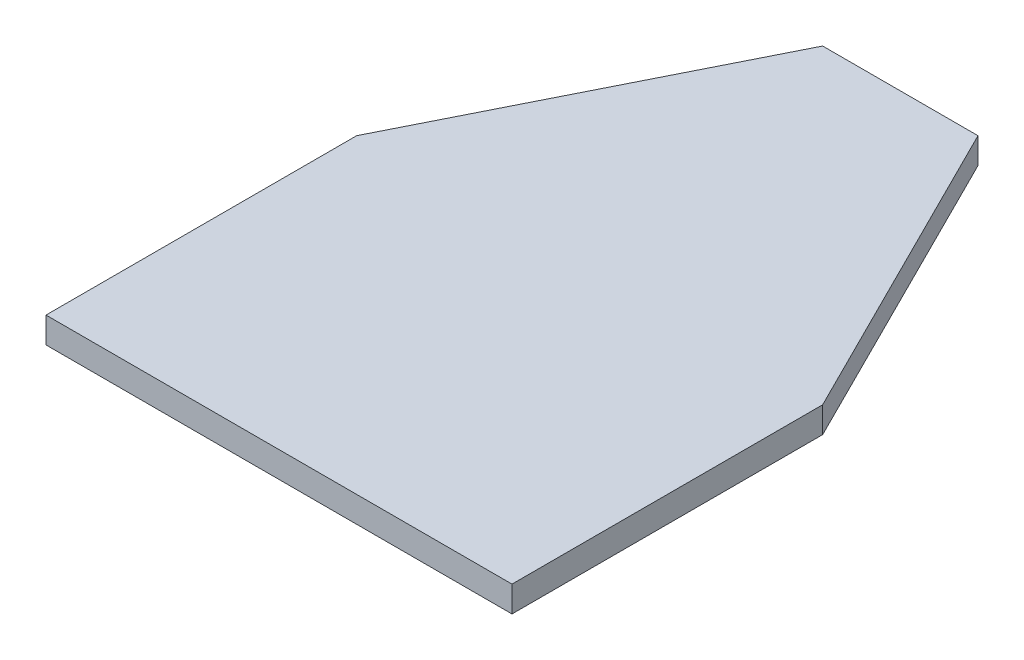
SolidWorks part; units mm, degrees
ref_plane "Front Plane" through (0, 0, 0) normal (0, 0, 1) x (1, 0, 0)
ref_plane "Top Plane" through (0, 0, 0) normal (0, 1, 0) x (1, 0, 0)
ref_plane "Right Plane" through (0, 0, 0) normal (1, 0, 0) x (0, 0, -1)
sketch "Sketch1" plane through (0, 0, 0) normal (0, 1, 0) x (1, 0, 0)
  line L0 (0, 0) -> (114.3, 0)
  line L1 (114.3, 0) -> (114.3, 76.2)
  line L2 (114.3, 76.2) -> (76.2, 152.4)
  line L3 (76.2, 152.4) -> (38.1, 152.4)
  line L4 (38.1, 152.4) -> (0, 76.2)
  line L5 (0, 76.2) -> (0, 0)
  line L6 (57.15, 0) -> (57.15, 152.4) construction
  line L7 (0, 57.15) -> (114.3, 57.15) construction
  line L8 (0, 19.05) -> (114.3, 19.05) construction
  dimension "D1" = 114.3
  dimension "D2" = 152.4
  dimension "D3" = 76.2
  dimension "D4" = 38.1
  dimension "D10" = 19.05
  dimension "D11" = 38.1
extrude "Extrude1" add sketch "Sketch1" along normal blind 6.35
